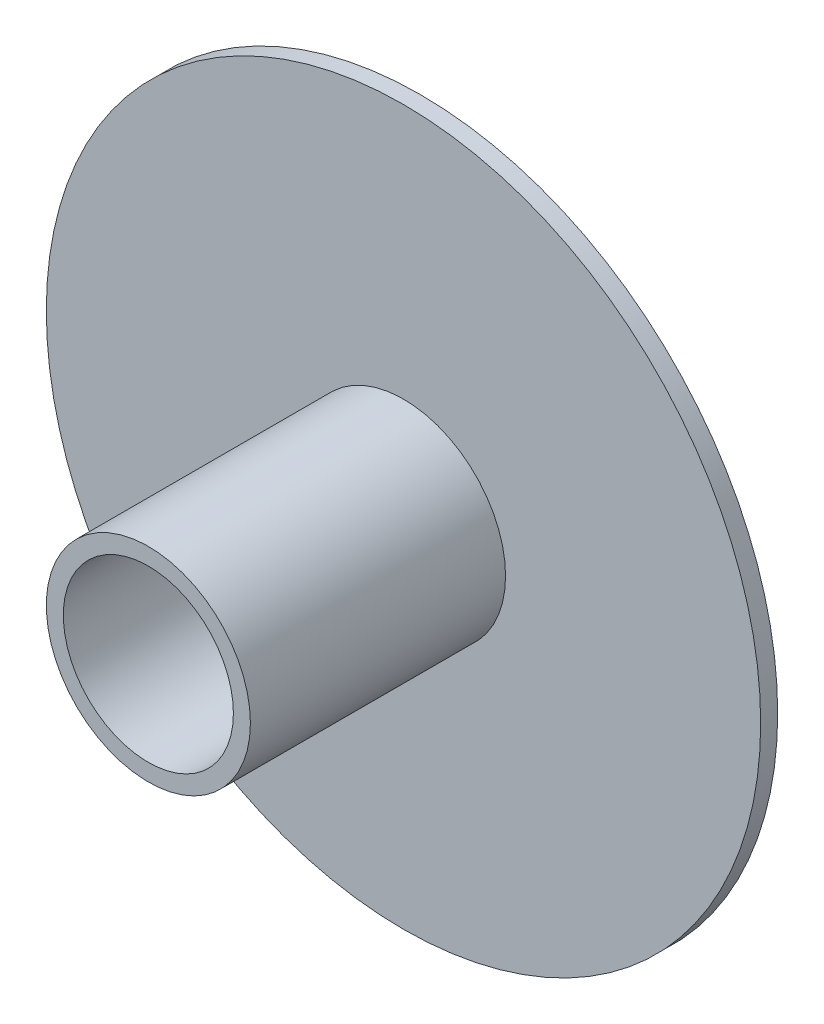
SolidWorks part; units mm, degrees
ref_plane "Front" through (0, 0, 0) normal (0, 0, 1) x (1, 0, 0)
ref_plane "Top" through (0, 0, 0) normal (0, 1, 0) x (1, 0, 0)
ref_plane "Right" through (0, 0, 0) normal (1, 0, 0) x (0, 0, -1)
sketch "Sketch1" plane through (0, 0, 0) normal (0, 0, 1) x (1, 0, 0)
  circle A0 centre (0, 0) radius 20 construction
  circle A1 centre (0, 0) radius 21
  dimension "D1" = 40
  dimension "D2" = 1
extrude "Boss-Extrude1" add sketch "Sketch1" along normal blind 1 contours A1
sketch "Sketch2" plane through (0, 0, 1) normal (0, 0, 1) x (1, 0, 0)
  circle A0 centre (0, 0) radius 5 construction
  circle A1 centre (0, 0) radius 6
  dimension "D2" = 1
  dimension "D1" = 10
extrude "Boss-Extrude2" add sketch "Sketch2" along normal blind 15
sketch "Sketch3" plane through (0, 0, 16) normal (0, 0, 1) x (1, 0, 0)
  circle A0 centre (0, 0) radius 5
  dimension "D1" = 10
extrude "Cut-Extrude1" cut sketch "Sketch3" against normal through all both and the other way through all contours A0
equation "\"D1@Sketch1\"=\"Cavity_Diameter\""
equation "\"Wall_Thickness\"= 1"
equation "\"Cavity_Diameter\"=40"
equation "\"D2@Sketch1\"=\"Wall_Thickness\""
equation "\"D1@Boss-Extrude1\"=\"Wall_Thickness\""
equation "\"Outlet_Diameter\"=10"
equation "\"D1@Sketch2\"=\"Outlet_Diameter\""
equation "\"Outlet_Length\"= 15"
equation "\"D1@Boss-Extrude2\"=\"Outlet_Length\""
equation "\"D1@Sketch3\"=\"Outlet_Diameter\""
